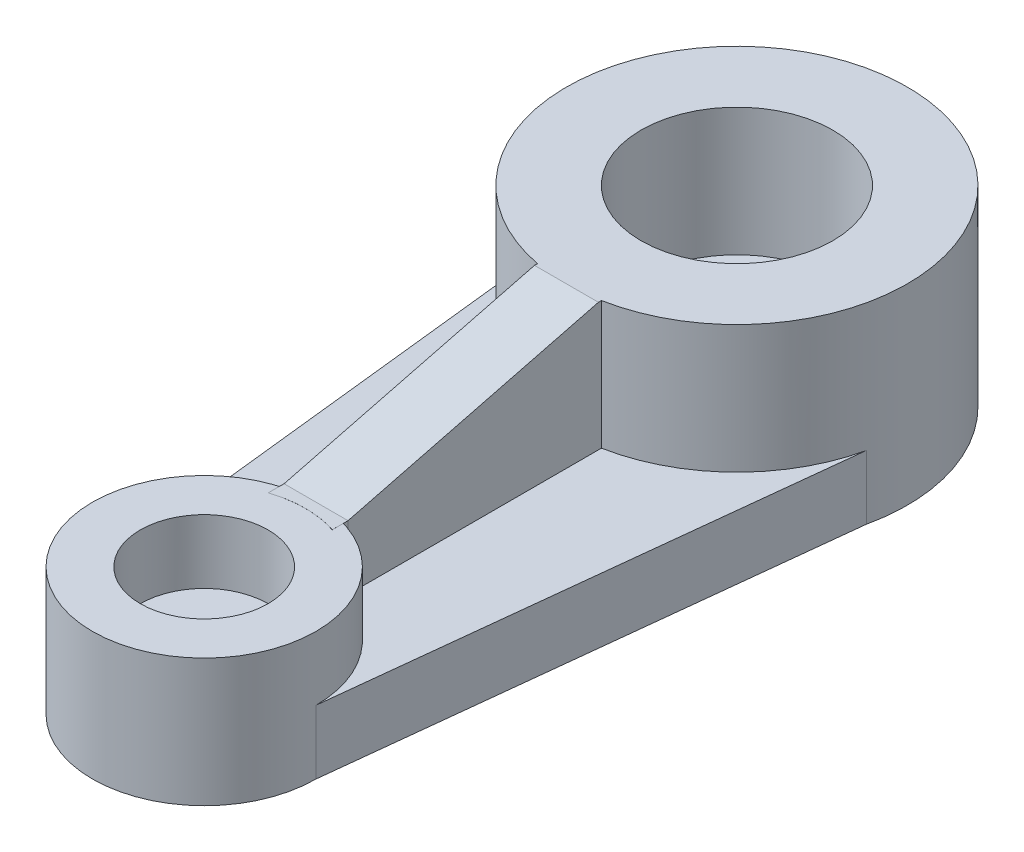
SolidWorks part; units mm, degrees
ref_plane "Front Plane" through (0, 0, 0) normal (0, 0, 1) x (1, 0, 0)
ref_plane "Top Plane" through (0, 0, 0) normal (0, 1, 0) x (1, 0, 0)
ref_plane "Right Plane" through (0, 0, 0) normal (1, 0, 0) x (0, 0, -1)
sketch "Sketch1" plane through (0, 0, 0) normal (0, 1, 0) x (1, 0, 0)
  circle A2 centre (0, 100) radius 32
  circle A3 centre (0, 100) radius 18
  dimension "D3" = 64
  dimension "D4" = 36
extrude "Boss-Extrude1" add sketch "Sketch1" along normal blind 36 contours A2 | A3
sketch "Sketch2" plane through (0, 0, 0) normal (0, 1, 0) x (1, 0, 0)
  circle A0 centre (0, 0) radius 21
  circle A1 centre (0, 0) radius 12
  circle A2 centre (0, 100) radius 32 construction
  dimension "D1" = 42
  dimension "D2" = 24
  dimension "D3" = 100
extrude "Boss-Extrude2" add sketch "Sketch2" along normal blind 24 separate body
sketch "Sketch7" plane through (0, 0, 0) normal (0, -1, 0) x (-1, 0, 0)
  line L0 (21, 0) -> (31.2349, 93.0442)
  line L2 (-21, 0) -> (-31.2349, 93.0442)
  circle A0 centre (0, 0) radius 21 construction
  arc A4 (-21, 0) -> (21, 0) centre (0, 0) ccw
  arc A6 (31.2349, 93.0442) -> (-31.2349, 93.0442) centre (0, 100) ccw
extrude "Boss-Extrude5" add sketch "Sketch7" against normal blind 12
ref_plane "Plane2" through (0, 0, 0) normal (1, 0, 0) x (0, 0, -1)
sketch "Sketch8" plane through (0, 0, 0) normal (1, 0, 0) x (0, 0, -1)
  line L2 (93.0442, 12) -> (0, 12) construction
  line L3 (68, 36) -> (68, 12) construction
  line L4 (68, 12) -> (20.943, 12)
  line L5 (20.943, 12) -> (21, 24)
  line L7 (68, 36) -> (68, 12)
  line L8 (68, 36) -> (21, 24)
extrude "Boss-Extrude8" add sketch "Sketch8" along normal mid plane 12 separate body
sketch "Sketch9" plane through (0, -0.0992, -20.8855) normal (0, 0.0048, 1) x (1, 0, 0)
  line L4 (-6, 24.0995) -> (-6, 12.0994)
  line L5 (-6, 12.0994) -> (6, 12.0994)
  line L6 (6, 12.0994) -> (6, 24.0995)
  line L7 (6, 24.0995) -> (-6, 24.0995)
  line L8 (-6, 24.0995) -> (-6, 12.0994)
  line L9 (-6, 12.0994) -> (6, 12.0994)
  line L10 (6, 12.0994) -> (6, 24.0995)
  line L11 (6, 24.0995) -> (-6, 24.0995)
  dimension "D1" = 0
extrude "Boss-Extrude12" add sketch "Sketch9" along normal offset from surface (2.9153 mm away) 2 separate body contours L8 L9 L10 L11
sketch "Sketch10" plane through (0, 0, -68) normal (0, 0, -1) x (-1, 0, 0)
  line L4 (6, 12) -> (6, 36)
  line L5 (6, 36) -> (-6, 36)
  line L6 (-6, 36) -> (-6, 12)
  line L7 (-6, 12) -> (6, 12)
  line L8 (6, 12) -> (6, 36)
  line L9 (6, 36) -> (-6, 36)
  line L10 (-6, 36) -> (-6, 12)
  line L11 (-6, 12) -> (6, 12)
  dimension "D1" = 0
extrude "Boss-Extrude13" add sketch "Sketch10" along normal up to next
